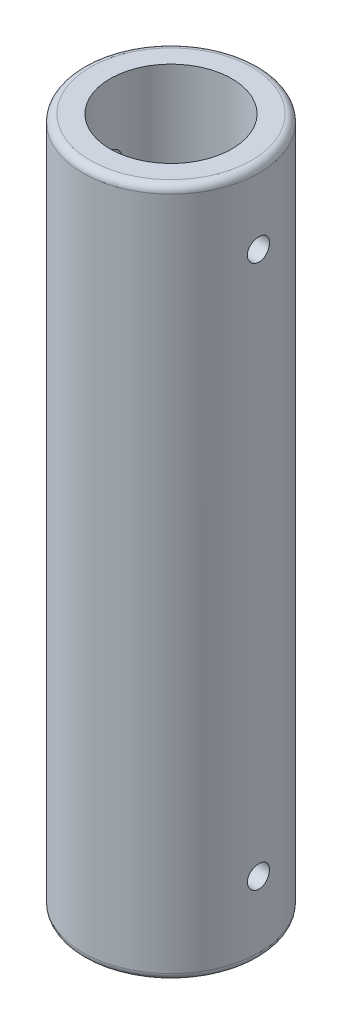
SolidWorks part; units mm, degrees
ref_plane "Front" through (0, 0, 0) normal (0, 0, 1) x (1, 0, 0)
ref_plane "Top" through (0, 0, 0) normal (0, 1, 0) x (1, 0, 0)
ref_plane "Right" through (0, 0, 0) normal (1, 0, 0) x (0, 0, -1)
sketch "Sketch1" plane through (0, 0, 0) normal (1, 0, 0) x (0, 0, -1)
  line L0 (0, 43.7565) -> (0, 0) construction
  line L1 (0, 0) -> (38.463, 0) construction
  line L2 (4.15, 24) -> (4.15, -24)
  line L3 (4.15, -23.5) -> (6, -23.5)
  line L4 (6, -24) -> (6, 24)
  line L5 (6, 23.5) -> (4.15, 23.5)
  line L6 (6, -24) -> (4.15, -24)
  line L7 (6, 24) -> (4.15, 24)
  point P10 (6, 0)
  dimension "D1" = 8.3
  dimension "D2" = 12
  dimension "D3" = 47
  dimension "D4" = 0.5
revolve "Revolve1" add sketch "Sketch1" angle 360 about L0
sketch "Sketch2" plane through (0, 0, 0) normal (1, 0, 0) x (0, 0, -1)
  line L0 (0, 18.5) -> (0, -18.5) construction
  circle A0 centre (0, 18.5) radius 0.75
  circle A1 centre (0, -18.5) radius 0.75
  point P5 (0, 0)
  dimension "D2" = 1.5
  dimension "D1" = 37
extrude "Cut-Extrude1" cut sketch "Sketch2" against normal through all both and the other way through all
fillet "Fillet1" radius 0.5 2 edges at (0, 23.5, 6) (0, -23.5, 6)
sketch "Sketch3" [suppressed] plane through (0, 0, 0) normal (1, 0, 0) x (0, 0, -1)
  line L0 (0, 0) -> (0, 45.0877) construction
  line L2 (4.15, 24) -> (6, 24)
  line L3 (4.15, 24) -> (4.15, 23)
  line L4 (4.15, 23) -> (6, 23)
  line L5 (6, 24) -> (6, 23)
  line L6 (6, -23) -> (4.15, -23)
  line L7 (6, -23) -> (6, -24)
  line L8 (6, -24) -> (4.15, -24)
  line L9 (4.15, -23) -> (4.15, -24)
revolve "Revolve2" [suppressed] add sketch "Sketch3" angle 360 about L0
fillet "Fillet2" [suppressed] radius 0.5
